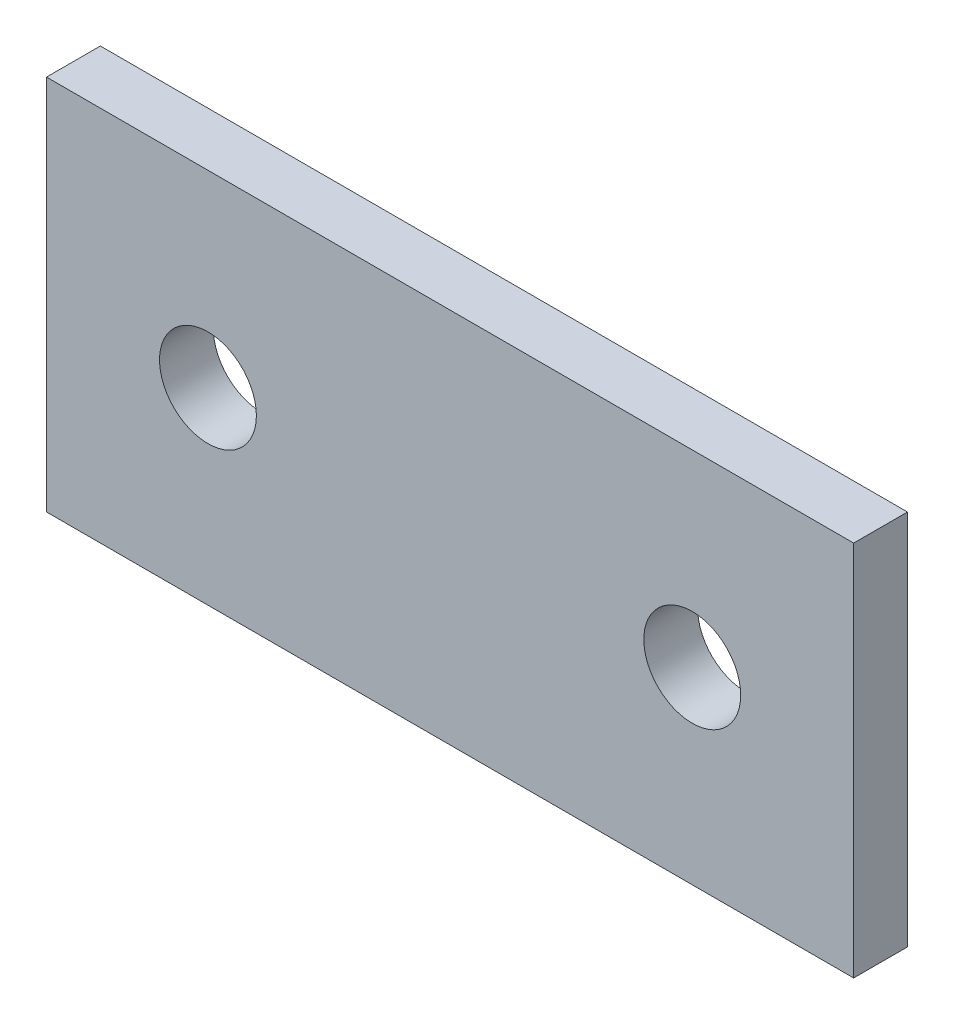
SolidWorks part; units mm, degrees
material "Plain Carbon Steel"
ref_plane "Front Plane" through (0, 0, 0) normal (0, 0, 1) x (1, 0, 0)
ref_plane "Top Plane" through (0, 0, 0) normal (0, 1, 0) x (1, 0, 0)
ref_plane "Right Plane" through (0, 0, 0) normal (1, 0, 0) x (0, 0, -1)
sketch "Sketch1" plane through (0, 0, 0) normal (0, 0, 1) x (1, 0, 0)
  line L1 (-75, 35) -> (75, 35)
  line L2 (-75, 35) -> (-75, -35)
  line L3 (-75, -35) -> (75, -35)
  line L4 (75, 35) -> (75, -35)
  line L5 (-75, 35) -> (75, -35) construction
  line L6 (-75, -35) -> (75, 35) construction
  circle A0 centre (45, 0) radius 9
  circle A1 centre (-45, 0) radius 9
  point P0 (0, 0)
  dimension "D3" = 30
  dimension "D4" = 18
  dimension "D5" = 30
  dimension "D6" = 18
  dimension "D1" = 70
  dimension "D2" = 150
extrude "Boss-Extrude1" add sketch "Sketch1" along normal mid plane 10
